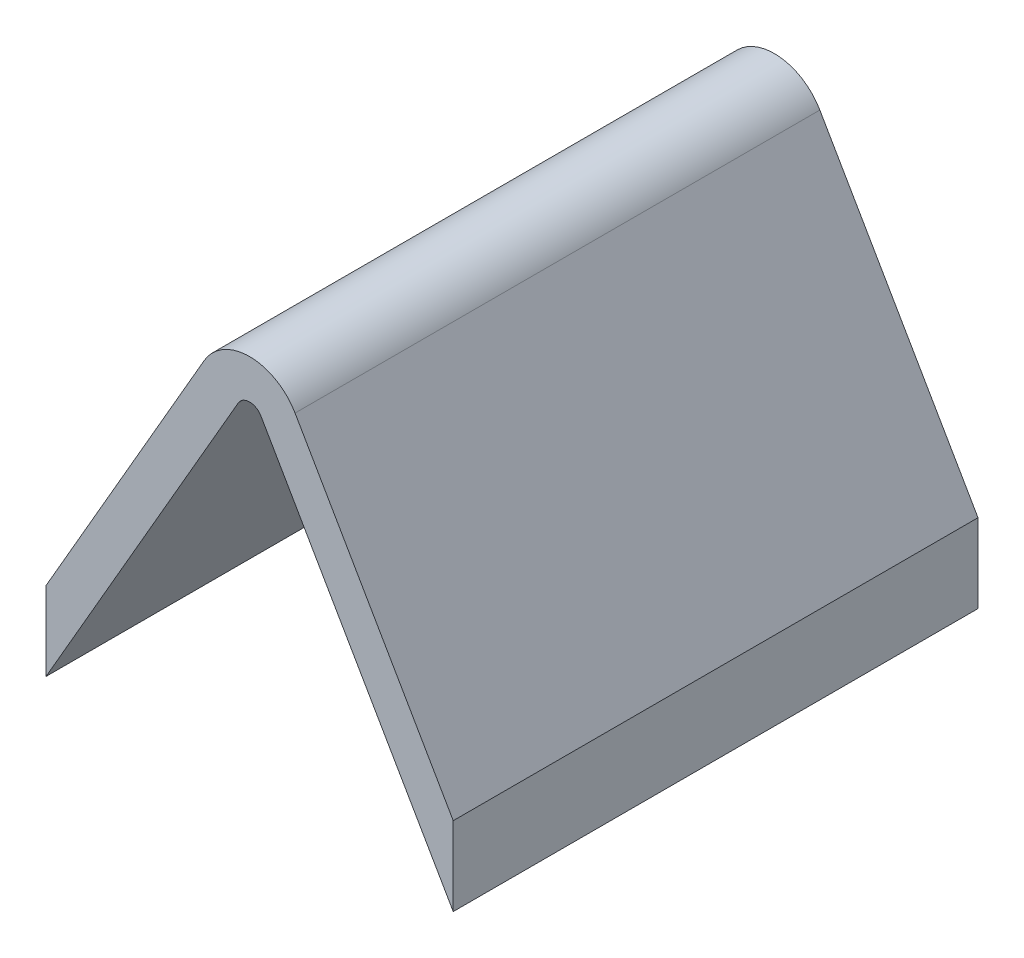
SolidWorks part; units mm, degrees
ref_plane "Front Plane" through (0, 0, 0) normal (0, 0, 1) x (1, 0, 0)
ref_plane "Top Plane" through (0, 0, 0) normal (0, 1, 0) x (1, 0, 0)
ref_plane "Right Plane" through (0, 0, 0) normal (1, 0, 0) x (0, 0, -1)
sketch "Sketch1" plane through (0, 0, 0) normal (0, 0, 1) x (1, 0, 0)
  line L0 (0, 125.9038) -> (0, 0) construction
  line L1 (-1.7321, 126.9038) -> (-75, 0) construction
  line L2 (-75, 0) -> (-77.5981, 1.5) construction
  line L3 (-77.5981, 1.5) -> (-4.3301, 128.4038) construction
  line L4 (-75, 0) -> (75, 0) construction
  line L5 (1.7321, 126.9038) -> (75, 0) construction
  line L6 (77.5981, 1.5) -> (4.3301, 128.4038) construction
  line L7 (75, 0) -> (77.5981, 1.5) construction
  line L8 (-77.5981, 1.5) -> (-4.3301, 128.4038)
  line L9 (4.3301, 128.4038) -> (77.5981, 1.5)
  line L10 (77.5981, 1.5) -> (77.5981, 31.5)
  line L11 (77.5981, 31.5) -> (17.3205, 135.9038)
  line L12 (-77.5981, 1.5) -> (-77.5981, 31.5)
  line L13 (-77.5981, 31.5) -> (-17.3205, 135.9038)
  arc A0 (1.7321, 126.9038) -> (-1.7321, 126.9038) centre (0, 125.9038) ccw construction
  arc A1 (4.3301, 128.4038) -> (-4.3301, 128.4038) centre (0, 125.9038) ccw construction
  arc A2 (-4.3301, 128.4038) -> (4.3301, 128.4038) centre (0, 125.9038) cw
  arc A3 (-17.3205, 135.9038) -> (17.3205, 135.9038) centre (0, 125.9038) cw
  point P17 (0, 0)
  dimension "D4" = 2
  dimension "D1" = 30
  dimension "D2" = 3
  dimension "D3" = 150
  dimension "D5" = 15
extrude "Boss-Extrude1" add sketch "Sketch1" along normal blind 200
